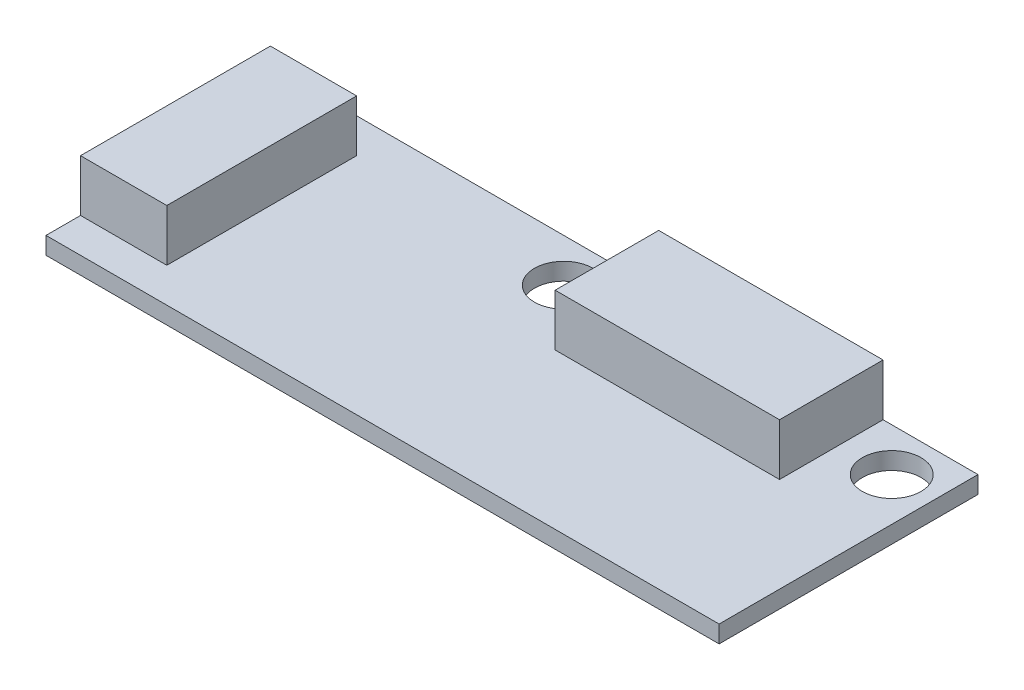
SolidWorks part; units mm, degrees
ref_plane "Front Plane" through (0, 0, 0) normal (0, 0, 1) x (1, 0, 0)
ref_plane "Top Plane" through (0, 0, 0) normal (0, 1, 0) x (1, 0, 0)
ref_plane "Right Plane" through (0, 0, 0) normal (1, 0, 0) x (0, 0, -1)
sketch "Sketch1" plane through (0, 0, 0) normal (0, 1, 0) x (1, 0, 0)
  line L1 (0, 0) -> (39, 0)
  line L2 (0, 0) -> (0, 15)
  line L3 (0, 15) -> (39, 15)
  line L4 (39, 0) -> (39, 15)
  dimension "D1" = 15
  dimension "D2" = 39
extrude "Boss-Extrude1" add sketch "Sketch1" along normal blind 1
hole_wizard "M3 Clearance Hole1" positions "Sketch2" profile "Sketch3" hole size "M3" standard "ANSI Metric" end condition through all
sketch "Sketch2" plane through (0, 1, 0) normal (0, 1, 0) x (1, 0, 0)
  line L0 (39, 12.5) -> (17.5, 12.5)
  line L1 (39, 0) -> (39, 15) construction
  line L3 (39, 15) -> (0, 15) construction
  point P0 (36.5, 12.5)
  point P2 (17.5, 12.5)
  point P10 (32.0047, 11.8712)
  point P11 (31.3384, 8.2111)
  point P12 (33.1205, 12.5255)
  dimension "D1" = 19
  dimension "D2" = 2.5
  dimension "D3" = 2.5
sketch "Sketch3" plane through (36.5, 1, -12.5) normal (1, 0, 0) x (0, 0, 1)
  line L0 (0, 0) -> (0, 1)
  line L1 (0, 1) -> (1.7, 1)
  line L2 (1.7, 1) -> (1.7, 0)
  line L5 (1.7, 0) -> (0, 0)
  line L11 (0, -6.35) -> (0, 107.95) construction
  dimension "Thru Hole Dia." = 3.4
  dimension "Thru Hole Depth" = 1
sketch "Sketch4" plane through (0, 1, 0) normal (0, 1, 0) x (1, 0, 0)
  line L0 (39, 15) -> (0, 15) construction
  line L1 (20.5, 15) -> (33.5, 15)
  line L2 (20.5, 15) -> (20.5, 9)
  line L3 (20.5, 9) -> (33.5, 9)
  line L4 (33.5, 15) -> (33.5, 9)
  line L5 (36.5, 12.5) -> (17.5, 12.5) construction
  line L6 (27, 12.5) -> (27, 9) construction
  point P12 (27, 4.2513)
  point P13 (27, 9)
  point P14 (27, 0)
  dimension "D1" = 13
  dimension "D2" = 6
extrude "Boss-Extrude2" add sketch "Sketch4" along normal blind 3
sketch "Sketch5" plane through (0, 1, 0) normal (0, 1, 0) x (1, 0, 0)
  line L0 (0, 15) -> (0, 0) construction
  line L1 (0, 13) -> (5, 13)
  line L2 (0, 13) -> (0, 2)
  line L3 (0, 2) -> (5, 2)
  line L4 (5, 13) -> (5, 2)
  point P6 (0, 7.5)
  dimension "D1" = 11
  dimension "D2" = 5
extrude "Boss-Extrude3" add sketch "Sketch5" along normal blind 3
